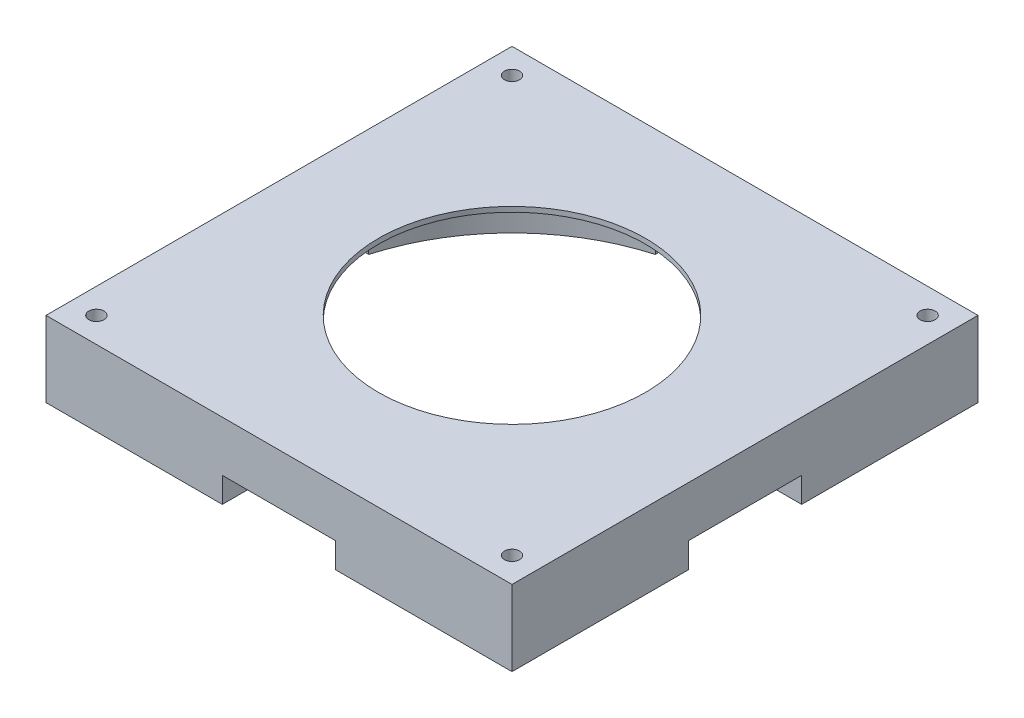
SolidWorks part; units mm, degrees
material "PE High Density"
ref_plane "Front Plane" through (0, 0, 0) normal (0, 0, 1) x (1, 0, 0)
ref_plane "Top Plane" through (0, 0, 0) normal (0, 1, 0) x (1, 0, 0)
ref_plane "Right Plane" through (0, 0, 0) normal (1, 0, 0) x (0, 0, -1)
sketch "Sketch1" plane through (0, 0, 0) normal (0, 0, 1) x (1, 0, 0)
  line L1 (53, -2) -> (82.5, -2)
  line L2 (82.5, -2) -> (82.5, -30)
  line L5 (82.5, -30) -> (85.5, -30)
  line L6 (85.5, -30) -> (85.5, 0)
  line L7 (85.5, 0) -> (53, 0)
  line L8 (53, -2) -> (53, 0)
  line L9 (0, 0) -> (53, 0) construction
  line L10 (0, 0) -> (0, -6.871) construction
  dimension "D1" = 3
  dimension "D3" = 2
  dimension "D5" = 30
  dimension "D6" = 82.5
  dimension "D7" = 53
revolve "Revolve1" add sketch "Sketch1" angle 360 about L10
sketch "Sketch2" plane through (0, -30, 0) normal (0, -1, 0) x (1, 0, 0)
  line L1 (-92.5, -92.5) -> (92.5, -92.5)
  line L2 (-92.5, -92.5) -> (-92.5, 92.5)
  line L3 (-92.5, 92.5) -> (92.5, 92.5)
  line L4 (92.5, -92.5) -> (92.5, 92.5)
  line L5 (-92.5, -92.5) -> (92.5, 92.5) construction
  line L6 (-92.5, 92.5) -> (92.5, -92.5) construction
  line L7 (-82.5, -82.5) -> (82.5, -82.5) construction
  line L8 (-82.5, -82.5) -> (-82.5, 82.5) construction
  line L9 (-82.5, 82.5) -> (82.5, 82.5) construction
  line L10 (82.5, -82.5) -> (82.5, 82.5) construction
  line L11 (-82.5, -82.5) -> (82.5, 82.5) construction
  line L12 (-82.5, 82.5) -> (82.5, -82.5) construction
  circle A0 centre (0, 0) radius 85.5
  circle A1 centre (0, 0) radius 85.5 construction
  circle A6 centre (-82.5, -82.5) radius 3
  circle A7 centre (82.5, -82.5) radius 3
  circle A8 centre (82.5, 82.5) radius 3
  circle A9 centre (-82.5, 82.5) radius 3
  dimension "D3" = 6
  dimension "D1" = 185
  dimension "D2" = 165
extrude "Boss-Extrude1" add sketch "Sketch2" against normal up to surface (30 mm away) up to face at (0, 0, 53)
sketch "Sketch3" plane through (-92.5, 0, 0) normal (-1, 0, 0) x (0, 0, 1)
  line L0 (92.5, -30) -> (-92.5, -30) construction
  line L1 (-22.5, -30) -> (22.5, -30)
  line L2 (-22.5, -30) -> (-22.5, -20)
  line L3 (-22.5, -20) -> (22.5, -20)
  line L4 (22.5, -30) -> (22.5, -20)
  line L5 (0, 0) -> (0, -20) construction
  line L6 (92.5, 0) -> (92.5, -30) construction
  dimension "D1" = 10
  dimension "D2" = 70
extrude "Cut-Extrude1" cut sketch "Sketch3" against normal through all
sketch "Sketch4" plane through (0, 0, -92.5) normal (0, 0, -1) x (-1, 0, 0)
  line L0 (92.5, -30) -> (-92.5, -30) construction
  line L1 (-22.5, -30) -> (22.5, -30)
  line L2 (-22.5, -30) -> (-22.5, -20)
  line L3 (-22.5, -20) -> (22.5, -20)
  line L4 (22.5, -30) -> (22.5, -20)
  line L5 (0, 0) -> (0, -20) construction
  line L6 (92.5, 0) -> (92.5, -30) construction
  dimension "D1" = 10
  dimension "D2" = 70
extrude "Cut-Extrude2" cut sketch "Sketch4" against normal through all
